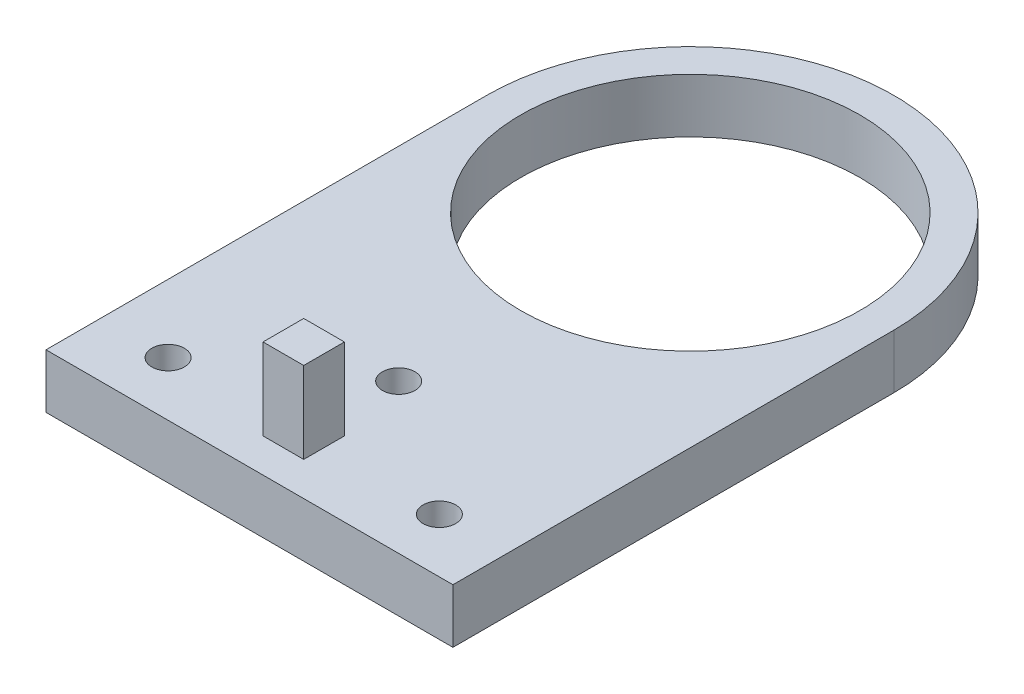
SolidWorks part; units mm, degrees
ref_plane "Front Plane" through (0, 0, 0) normal (0, 0, 1) x (1, 0, 0)
ref_plane "Top Plane" through (0, 0, 0) normal (0, 1, 0) x (1, 0, 0)
ref_plane "Right Plane" through (0, 0, 0) normal (1, 0, 0) x (0, 0, -1)
sketch "Sketch1" plane through (0, 0, 0) normal (0, 1, 0) x (1, 0, 0)
  line L0 (-15, 0) -> (15, 0)
  line L1 (-15, 0) -> (-15, 32.5)
  line L2 (15, 0) -> (15, 32.5)
  arc A0 (-15, 32.5) -> (15, 32.5) centre (0, 32.5) cw
  point P6 (0, 0)
  point P7 (11.4741, 30)
  point P8 (-12.5, 29.1071)
  dimension "D1" = 32.5
  dimension "D2" = 30
extrude "Boss-Extrude1" add sketch "Sketch1" along normal blind 4
sketch "Sketch2" plane through (0, 4, 0) normal (0, 1, 0) x (1, 0, 0)
  circle A0 centre (0, 32.5) radius 12.5
  dimension "D1" = 25
extrude "Cut-Extrude1" cut sketch "Sketch2" against normal up to next
sketch "Sketch3" plane through (0, 4, 0) normal (0, 1, 0) x (1, 0, 0)
  line L0 (-15, 0) -> (15, 0) construction
  line L1 (-1.5, 5.5) -> (1.5, 5.5)
  line L2 (-1.5, 5.5) -> (-1.5, 2.5)
  line L3 (-1.5, 2.5) -> (1.5, 2.5)
  line L4 (1.5, 5.5) -> (1.5, 2.5)
  point P4 (0, 2.5)
  point P6 (1.5, 4)
  point P7 (0, 0)
  point P9 (0, 0)
  dimension "D1" = 4
  dimension "D2" = 3
extrude "Boss-Extrude2" add sketch "Sketch3" along normal blind 6
hole_wizard "CSK for M2 Countersunk Flat Head Screw1" positions "Sketch4" profile "Sketch5" countersink size "M2" standard "DIN"
sketch "Sketch4" plane through (0, 0, 0) normal (0, -1, 0) x (-1, 0, 0)
  line L0 (15, 0) -> (-15, 0) construction
  point P0 (-10, 4)
  point P2 (10, 4)
  point P4 (0, 11)
  point P7 (0, 0)
  point P8 (0, 0)
  dimension "D1" = 4
  dimension "D2" = 10
  dimension "D3" = 10
  dimension "D4" = 11
sketch "Sketch5" plane through (10, 0, -4) normal (1, 0, 0) x (0, 0, -1)
  line L0 (0, 0) -> (0, 5.921)
  line L1 (0, 5.921) -> (1.2, 5.2)
  line L2 (1.2, 5.2) -> (1.2, 1.5)
  line L3 (1.2, 1.5) -> (2.7, 0)
  line L5 (2.7, 0) -> (0, 0)
  line L6 (-1.2, 1.5) -> (-2.7, 0) construction
  line L10 (0, 5.921) -> (-1.2, 5.2) construction
  line L11 (0, -6.35) -> (0, 107.95) construction
  dimension "Hole Dia." = 2.4
  dimension "Hole Depth" = 5.2
  dimension "Near C'Sink Dia." = 5.4
  dimension "Near C'Sink Angle" = 90
  dimension "Drill Angle" = 118
